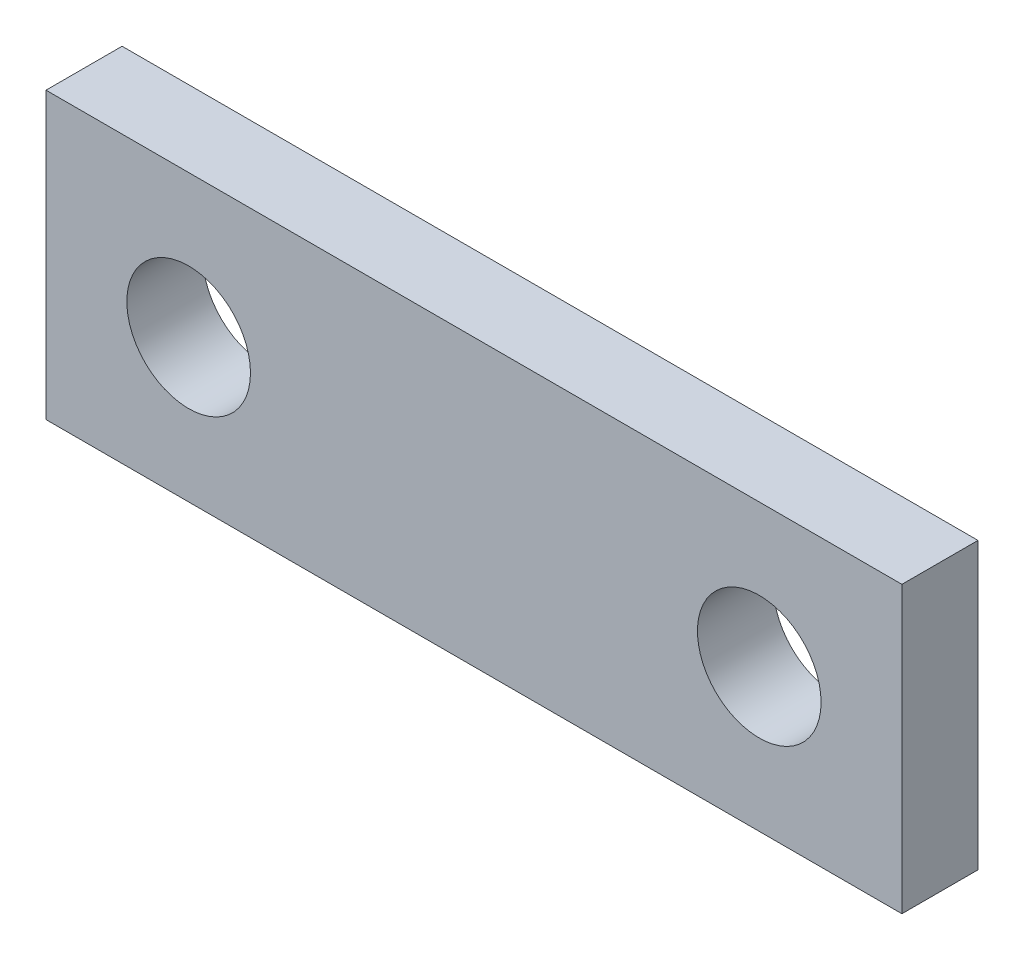
SolidWorks part; units mm, degrees
ref_plane "前视基准面" through (0, 0, 0) normal (0, 0, 1) x (1, 0, 0)
ref_plane "上视基准面" through (0, 0, 0) normal (0, 1, 0) x (1, 0, 0)
ref_plane "右视基准面" through (0, 0, 0) normal (1, 0, 0) x (0, 0, -1)
sketch "草图1" plane through (0, 0, 0) normal (0, 0, 1) x (1, 0, 0)
  line L0 (-910, 15) -> (49090, 15) construction
  line L1 (0, 0) -> (90, 0)
  line L2 (0, 0) -> (0, 30)
  line L3 (0, 30) -> (90, 30)
  line L4 (90, 0) -> (90, 30)
  line L5 (45, -970) -> (45, 49030) construction
  circle A0 centre (15, 15) radius 6.5
  circle A1 centre (75, 15) radius 6.5
  point P8 (90, 15)
  point P11 (45, 30)
  dimension "D5" = 13
  dimension "D6" = 13
  dimension "D1" = 90
  dimension "D2" = 30
  dimension "D3" = 30
  dimension "D4" = 30
extrude "凸台-拉伸1" add sketch "草图1" along normal blind 8
